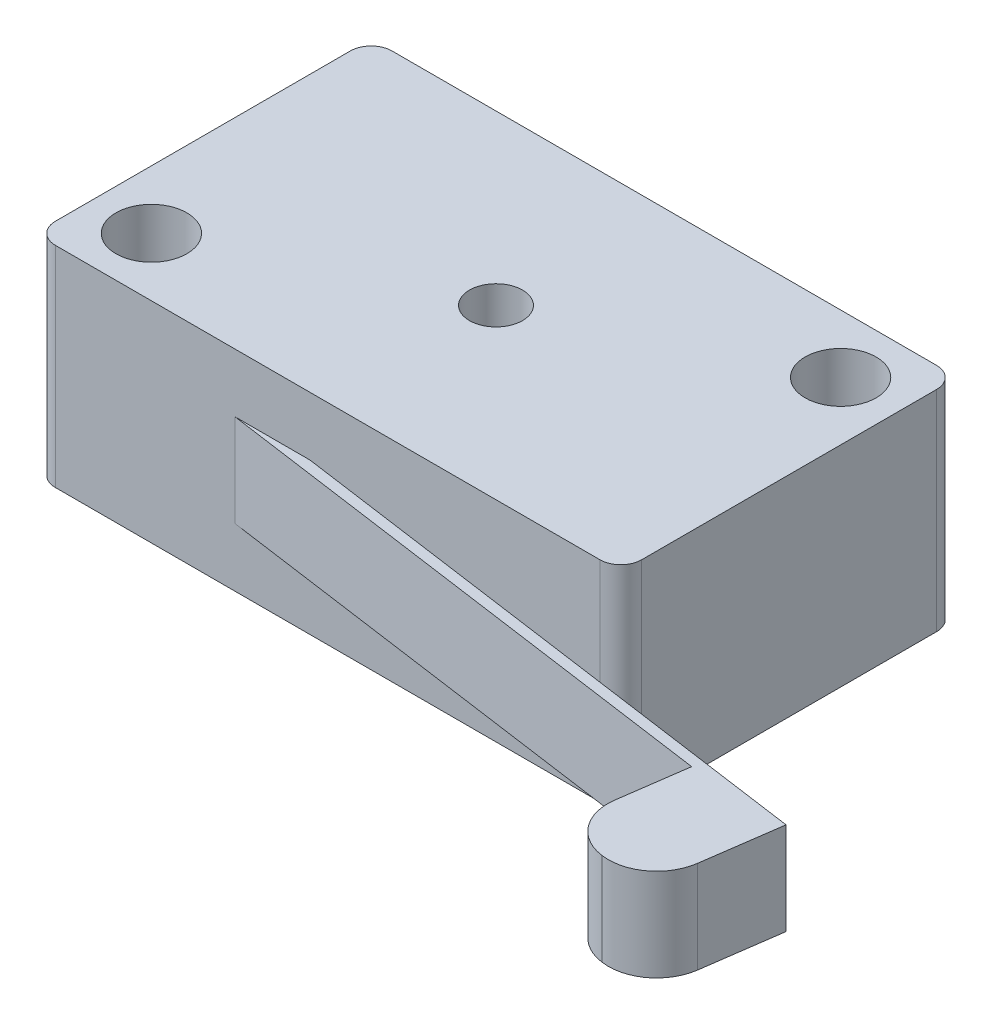
SolidWorks part; units mm, degrees
ref_plane "Front Plane" through (0, 0, 0) normal (0, 0, 1) x (1, 0, 0)
ref_plane "Top Plane" through (0, 0, 0) normal (0, 1, 0) x (1, 0, 0)
ref_plane "Right Plane" through (0, 0, 0) normal (1, 0, 0) x (0, 0, -1)
sketch "Sketch1" plane through (0, 0, 0) normal (0, 1, 0) x (1, 0, 0)
  line L0 (-2.645, -8.065) -> (25.6569, -12.0426) construction
  line L1 (-14.045, -8.065) -> (14.045, -8.065)
  line L2 (-14.045, -8.065) -> (-14.045, 8.065)
  line L3 (-14.045, 8.065) -> (14.045, 8.065)
  line L4 (14.045, -8.065) -> (14.045, 8.065)
  line L5 (-14.045, -8.065) -> (14.045, 8.065) construction
  line L6 (-14.045, 8.065) -> (14.045, -8.065) construction
  point P0 (0, 0)
  point P6 (-2.645, -8.065)
  dimension "D1" = 28.09
  dimension "D2" = 16.13
  dimension "D3" = 11.4
  dimension "D4" = 28.58
  dimension "D5" = 8
extrude "Boss-Extrude1" add sketch "Sketch1" along normal blind 10.05
sketch "Sketch2" plane through (0, 0, 0) normal (0, -1, 0) x (1, 0, 0)
  line L2 (-9.194, -4.8989) -> (9.194, -4.8989) construction
  line L3 (-9.194, -4.8989) -> (-9.194, 4.8989) construction
  line L4 (-9.194, 4.8989) -> (9.194, 4.8989) construction
  line L7 (9.194, -4.8989) -> (9.194, 4.8989) construction
  line L8 (-9.194, -4.8989) -> (9.194, 4.8989) construction
  line L9 (-9.194, 4.8989) -> (9.194, -4.8989) construction
  point P0 (0, 0)
ref_plane "Plane1" through (0, 5.025, 0) normal (0, 1, 0) x (1, 0, 0)
sketch "Sketch3" plane through (0, 5.025, 0) normal (0, 1, 0) x (1, 0, 0)
  line L0 (25.6569, -12.0426) -> (25.6221, -12.2901)
  line L1 (25.6221, -12.2901) -> (-4.4413, -8.065)
  line L2 (-4.4413, -8.065) -> (-4.3717, -7.5699)
  line L3 (-4.3717, -7.5699) -> (25.6917, -11.795)
  line L5 (25.6917, -11.795) -> (25.6569, -12.0426)
  line L6 (-2.645, -8.065) -> (25.6569, -12.0426) construction
  line L8 (-14.045, -8.065) -> (14.045, -8.065) construction
  dimension "D1" = 0.5
extrude "Boss-Extrude2" add sketch "Sketch3" along normal mid plane 4.43
fillet "Fillet1" radius 1 4 edges at (-14.045, 5.025, -8.065) (-14.045, 5.025, 8.065) (14.045, 5.025, -8.065) (14.045, 5.025, 8.065)
sketch "Sketch4" plane through (0, 5.025, 0) normal (0, 1, 0) x (1, 0, 0)
  line L0 (-14.045, 7.065) -> (-14.045, -7.065) construction
  line L1 (-11.245, -5.265) -> (11.245, -5.265) construction
  line L2 (-11.245, -5.265) -> (-11.245, 5.265) construction
  line L3 (-11.245, 5.265) -> (11.245, 5.265) construction
  line L4 (11.245, -5.265) -> (11.245, 5.265) construction
  line L5 (-11.245, -5.265) -> (11.245, 5.265) construction
  line L6 (-11.245, 5.265) -> (11.245, -5.265) construction
  line L7 (13.045, 8.065) -> (-13.045, 8.065) construction
  circle A0 centre (11.245, 5.265) radius 1.7
  circle A1 centre (-11.245, -5.265) radius 1.7
  circle A2 centre (0, 0) radius 1.27
  point P4 (0, 0)
  dimension "D3" = 3.4
  dimension "D4" = 2.54
  dimension "D1" = 2.8
  dimension "D2" = 2.8
extrude "Cut-Extrude1" cut sketch "Sketch4" against normal through all both and the other way through all
sketch "Sketch6" plane through (-1.1975, 0, 8.5209) normal (-0.1392, 0, 0.9903) x (0.9903, 0, 0.1392)
  line L0 (-3.2757, 2.81) -> (27.0832, 2.81) construction
  line L1 (27.0832, 7.24) -> (22.4332, 7.24)
  line L2 (27.0832, 7.24) -> (27.0832, 2.81)
  line L3 (27.0832, 2.81) -> (22.4332, 2.81)
  line L4 (22.4332, 7.24) -> (22.4332, 2.81)
  dimension "D1" = 4.65
extrude "Boss-Extrude3" add sketch "Sketch6" along normal blind 5.56
fillet "Fillet2" radius 2.3 2 edges at (20.2435, 5.025, 17.1489) (24.8483, 5.025, 17.796)
